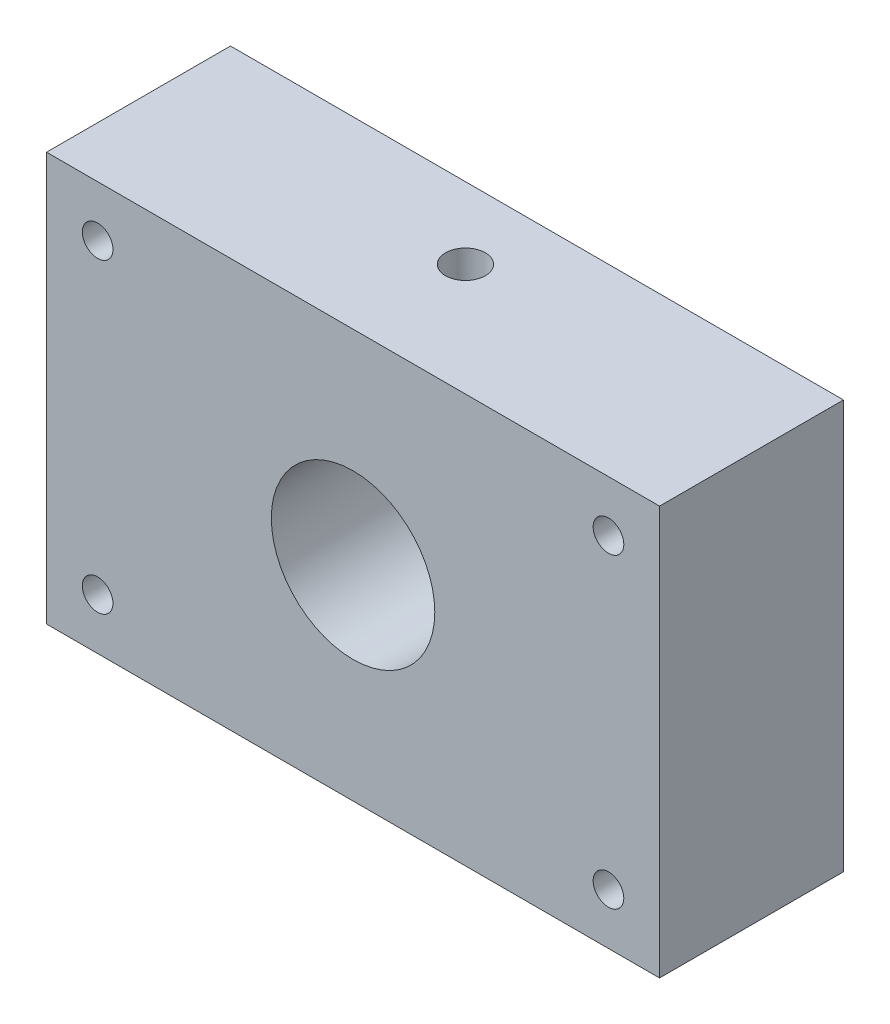
SolidWorks part; units mm, degrees
ref_plane "Ön Düzlem" through (0, 0, 0) normal (0, 0, 1) x (1, 0, 0)
ref_plane "Üst Düzlem" through (0, 0, 0) normal (0, 1, 0) x (1, 0, 0)
ref_plane "Sağ Düzlem" through (0, 0, 0) normal (1, 0, 0) x (0, 0, -1)
sketch "Çizim1" plane through (0, 0, 0) normal (0, 0, 1) x (1, 0, 0)
  line L1 (-30, 20) -> (30, 20)
  line L2 (-30, 20) -> (-30, -20)
  line L3 (-30, -20) -> (30, -20)
  line L4 (30, 20) -> (30, -20)
  circle A0 centre (-25, 15) radius 1.5
  circle A1 centre (0, 0) radius 8
  circle A2 centre (25, 15) radius 1.5
  circle A3 centre (25, -15) radius 1.5
  circle A4 centre (-25, -15) radius 1.5
  point P15 (0, 0)
  point P16 (0, 0)
  point P17 (0, 0)
  point P18 (0, 0)
  dimension "D1" = 16
  dimension "D2" = 60
  dimension "D6" = 3
  dimension "D3" = 30
  dimension "D4" = 20
  dimension "D5" = 5
  dimension "D7" = 5
  dimension "D8" = 5
  dimension "D9" = 5
  dimension "D10" = 40
extrude "Yükseklik-Ekstrüzyon1" add sketch "Çizim1" along normal blind 18
sketch "Çizim2" plane through (0, 20, 0) normal (0, 1, 0) x (1, 0, 0)
  circle A0 centre (0, -7) radius 1.95
  point P2 (0, 0)
  dimension "D1" = 3.9
  dimension "D2" = 7
extrude "Kes-Ekstrüzyon1" cut sketch "Çizim2" against normal blind 28
